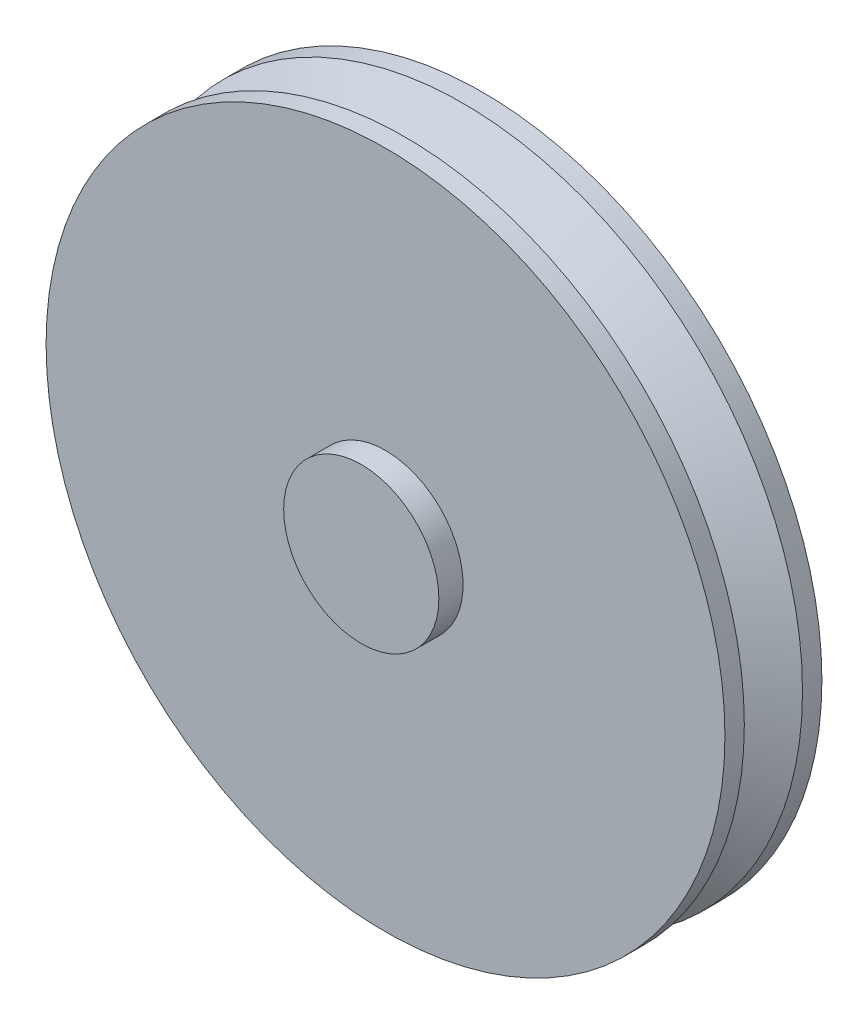
SolidWorks part; units mm, degrees
ref_plane "Front Plane" through (0, 0, 0) normal (0, 0, 1) x (1, 0, 0)
ref_plane "Top Plane" through (0, 0, 0) normal (0, 1, 0) x (1, 0, 0)
ref_plane "Right Plane" through (0, 0, 0) normal (1, 0, 0) x (0, 0, -1)
sketch "Sketch1" plane through (0, 0, 0) normal (0, 0, 1) x (1, 0, 0)
  circle A0 centre (0, 0) radius 44.45
  point P2 (0, 0)
  point P4 (0, 0)
extrude "Boss-Extrude1" add sketch "Sketch1" along normal blind 2.54
ref_plane "Plane2" through (0, 0, 6.35) normal (0, 0, 1) x (1, 0, 0)
sketch "Sketch2" plane through (0, 0, 6.35) normal (0, 0, 1) x (1, 0, 0)
  circle A0 centre (0, 0) radius 38.1
  point P2 (0, 0)
loft "Loft1" add profiles "Sketch2" section edge at (44.45, 0, 2.54) section "Sketch2"
mirror "Mirror3" about plane through (0, 0, 6.35) normal (0, 0, 1) of bodies 102
sketch "Sketch3" plane through (0, 0, 12.7) normal (0, 0, 1) x (1, 0, 0)
  circle A0 centre (0, 0) radius 10.16
extrude "Boss-Extrude2" add sketch "Sketch3" along normal blind 3.175
